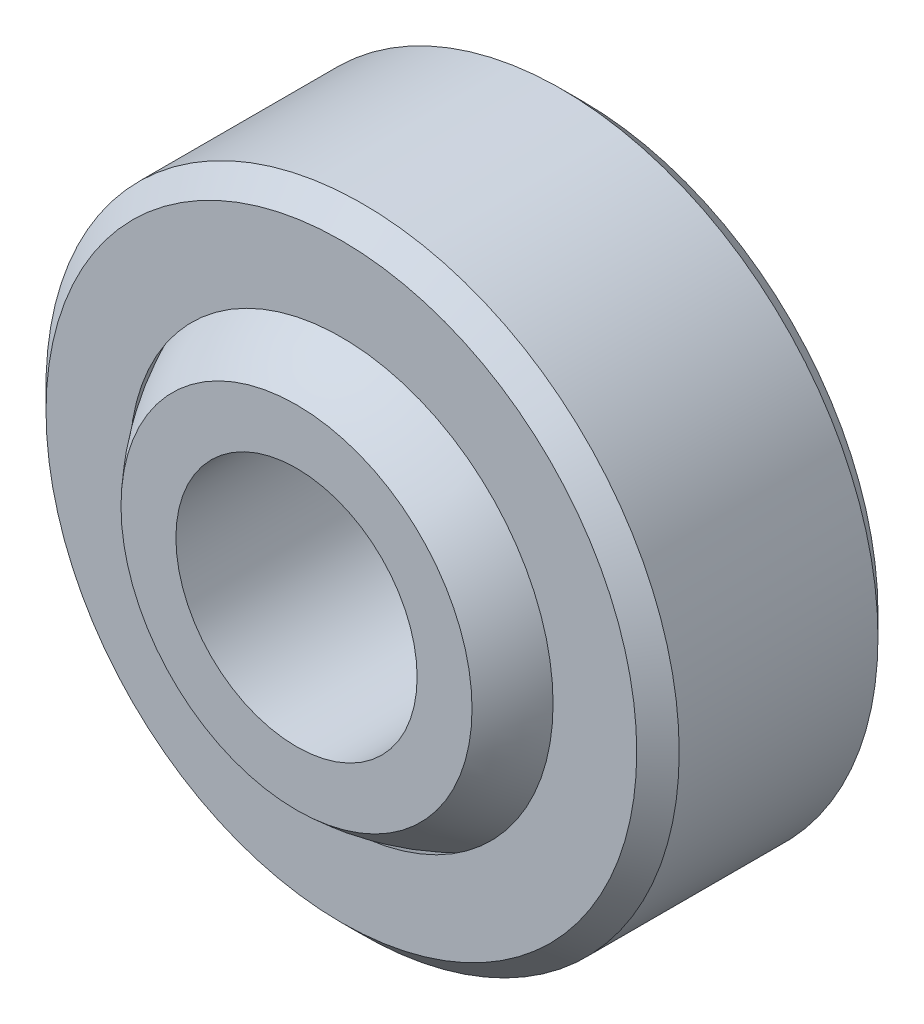
SolidWorks part; units mm, degrees
ref_plane "Front" through (0, 0, 0) normal (0, 0, 1) x (1, 0, 0)
ref_plane "Top" through (0, 0, 0) normal (0, 1, 0) x (1, 0, 0)
ref_plane "Right" through (0, 0, 0) normal (1, 0, 0) x (0, 0, -1)
sketch "Sketch1" plane through (0, 0, 0) normal (0, 0, 1) x (1, 0, 0)
  circle A0 centre (0, 0) radius 3.175 construction
  circle A1 centre (0, 0) radius 6.35 construction
  circle A2 centre (0, 0) radius 6.4135 construction
  circle A3 centre (0, 0) radius 8.3337
  dimension "D1" = 12.827
  dimension "D OD" = 16.6675
  dimension "B Hole Dia" = 6.35
  dimension "Ball Dia" = 12.7
extrude "Extrude1" add sketch "Sketch1" along normal mid plane 6.35
sketch "Sketch2" plane through (0, 0, 0) normal (0, 0, 1) x (1, 0, 0)
  line L0 (0, 6.4135) -> (0, -6.4135)
  line L1 (0, 6.4135) -> (0, 8.3337) construction
  circle A0 centre (0, 0) radius 6.4135 construction
  arc A1 (0, -6.4135) -> (0, 6.4135) centre (0, 0) ccw
  circle A2 centre (0, 0) radius 8.3337 construction
revolve "Cut-Revolve1" cut sketch "Sketch2" angle 360 about L1
sketch "Sketch3" plane through (0, 0, 0) normal (0, 0, 1) x (1, 0, 0)
  line L0 (0, 6.35) -> (0, -6.35)
  line L1 (0, 6.35) -> (0, 8.3337) construction
  circle A0 centre (0, 0) radius 6.35 construction
  arc A1 (0, -6.35) -> (0, 6.35) centre (0, 0) ccw
  circle A2 centre (0, 0) radius 8.3337 construction
revolve "Revolve1" add sketch "Sketch3" angle 360 about L1
sketch "Sketch4" plane through (0, 0, 0) normal (0, 0, 1) x (1, 0, 0)
  circle A0 centre (0, 0) radius 3.175 construction
  circle A1 centre (0, 0) radius 3.175
extrude "Cut-Extrude1" cut sketch "Sketch4" against normal through all and the other way through all
sketch "Sketch5" plane through (0, 0, 0) normal (1, 0, 0) x (0, 0, -1)
  line L0 (-4.3561, 8.3337) -> (4.3561, 8.3337) construction
  line L1 (-4.3561, 8.3337) -> (-5.4993, 8.3337)
  line L2 (-4.3561, 8.3337) -> (-4.3561, -8.3337)
  line L3 (-4.3561, -8.3337) -> (-5.4993, -8.3337)
  line L4 (-5.4993, 8.3337) -> (-5.4993, -8.3337)
  line L5 (4.3561, -8.3337) -> (5.4993, -8.3337)
  line L6 (4.3561, -8.3337) -> (4.3561, 8.3337)
  line L7 (4.3561, 8.3337) -> (5.4993, 8.3337)
  line L8 (5.4993, -8.3337) -> (5.4993, 8.3337)
  line L16 (3.175, 8.3337) -> (-3.175, 8.3337) construction
  line L17 (5.4993, -3.175) -> (5.4993, 3.175) construction
  line L18 (-5.4993, -3.175) -> (-5.4993, 3.175) construction
  line L19 (-4.3561, -8.3337) -> (4.3561, -8.3337) construction
  line L20 (-3.175, -8.3337) -> (3.175, -8.3337) construction
  line L21 (0, 0) -> (-4.3561, 1.0458) construction
  line L22 (0, 0) -> (-4.3561, -1.0458) construction
  dimension "W ball Width" = 8.7122
  dimension "Mis Angle" = 27
extrude "Cut-Extrude2" cut sketch "Sketch5" against normal through all and the other way through all
chamfer "Chamfer1" distance 0.5588 angle 45 2 edges at (8.3337, 0, 3.175) (8.3337, 0, -3.175)
sketch "Sketch7" plane through (0, 0, 0) normal (1, 0, 0) x (0, 0, -1)
  line L0 (0, 0) -> (-4.3561, -1.0458) construction
  line L1 (0, 0) -> (-4.3561, 1.0458) construction
  line L2 (0, 0) -> (-4.3561, -1.0458) construction
  line L3 (0, 0) -> (-4.3561, 1.0458) construction
equation "\"D1@Sketch1\"=\"Ball Dia@Sketch1\"*1.01"
